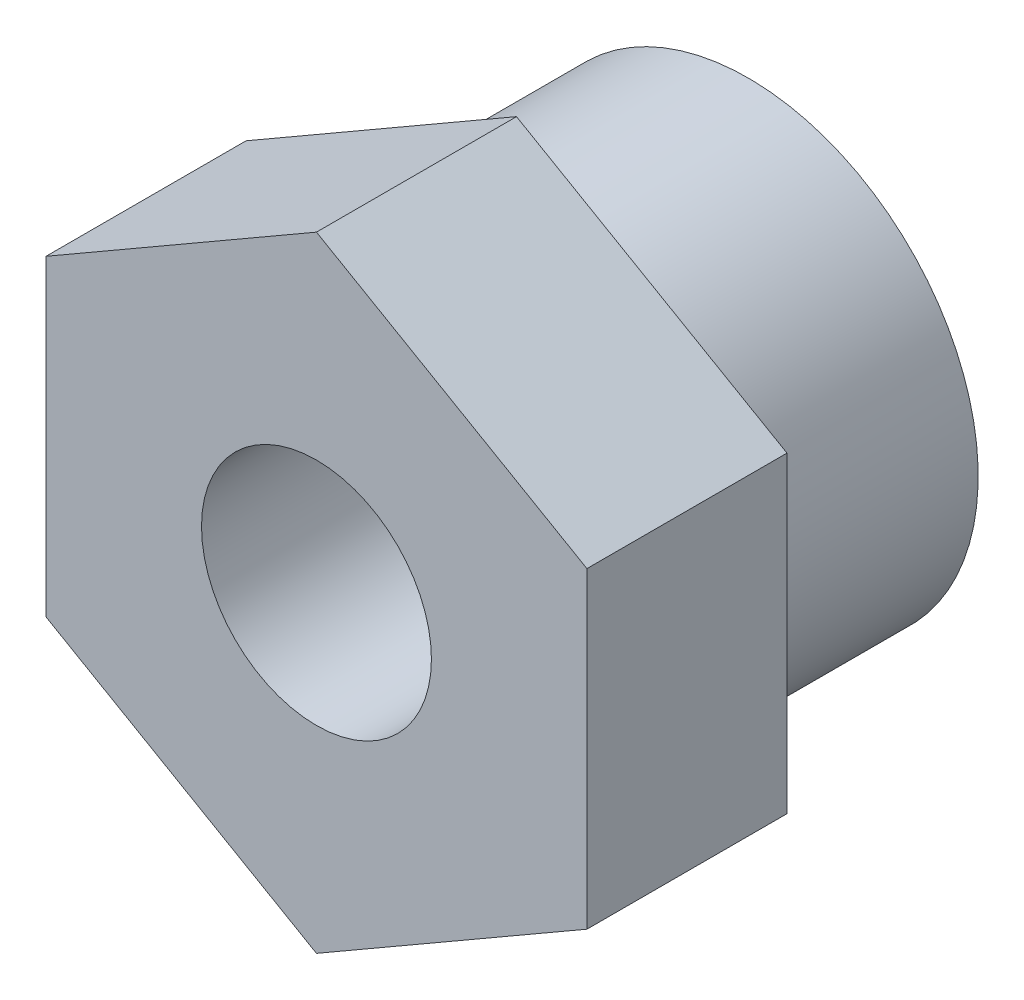
SolidWorks part; units mm, degrees
material "Plain Carbon Steel"
ref_plane "Piano frontale" through (0, 0, 0) normal (0, 0, 1) x (1, 0, 0)
ref_plane "Piano superiore" through (0, 0, 0) normal (0, 1, 0) x (1, 0, 0)
ref_plane "Piano destro" through (0, 0, 0) normal (1, 0, 0) x (0, 0, -1)
sketch "Schizzo1" plane through (0, 0, 0) normal (0, 0, 1) x (1, 0, 0)
  circle A0 centre (0, 0) radius 17.25
  dimension "D1" = 34.5
extrude "Estrusione-Estrusione1" add sketch "Schizzo1" along normal blind 23.85
sketch "Schizzo2" plane through (0, 0, 23.85) normal (0, 0, 1) x (1, 0, 0)
  line L1 (0, 17.25) -> (-14.9389, 8.625)
  line L2 (-14.9389, 8.625) -> (-14.9389, -8.625)
  line L3 (-14.9389, -8.625) -> (0, -17.25)
  line L4 (0, -17.25) -> (14.9389, -8.625)
  line L5 (14.9389, -8.625) -> (14.9389, 8.625)
  line L6 (14.9389, 8.625) -> (0, 17.25)
  circle A0 centre (0, 0) radius 14.9389 construction
  circle M1 centre (0, 0) radius 17.25
extrude "Taglio-Estrusione1" cut sketch "Schizzo2" against normal blind 11.05 contours L1 M1 | L2 M1 | L3 M1 | L4 M1 | L5 M1 | L6 M1
hole_wizard "Foro Ø25.5 (12.7)-1" positions "Schizzo3" profile "Schizzo4" hole size "Ø25.5" standard "ISO" end condition through all
sketch "Schizzo3" plane through (0, 0, 23.85) normal (0, 0, 1) x (1, 0, 0)
  point P0 (0, 0)
sketch "Schizzo4" plane through (0, 0, 23.85) normal (1, 0, 0) x (0, -1, 0)
  line L0 (0, 0) -> (0, 23.85)
  line L1 (0, 23.85) -> (6.35, 23.85)
  line L2 (6.35, 23.85) -> (6.35, 0)
  line L5 (6.35, 0) -> (0, 0)
  line L11 (0, -6.35) -> (0, 107.95) construction
  dimension "Thru Hole Dia." = 12.7
  dimension "Thru Hole Depth" = 23.85
sketch "Schizzo5" plane through (0, 0, 0) normal (0, 0, -1) x (-1, 0, 0)
  circle A0 centre (0, 0) radius 12.7
  circle M2 centre (0, 0) radius 17.25
  dimension "D1" = 25.4
extrude "Taglio-Estrusione2" cut sketch "Schizzo5" against normal blind 12.8 contours A0 M2
cosmetic thread "Filettatura cosmetica1" parameters "D2"=20.588
